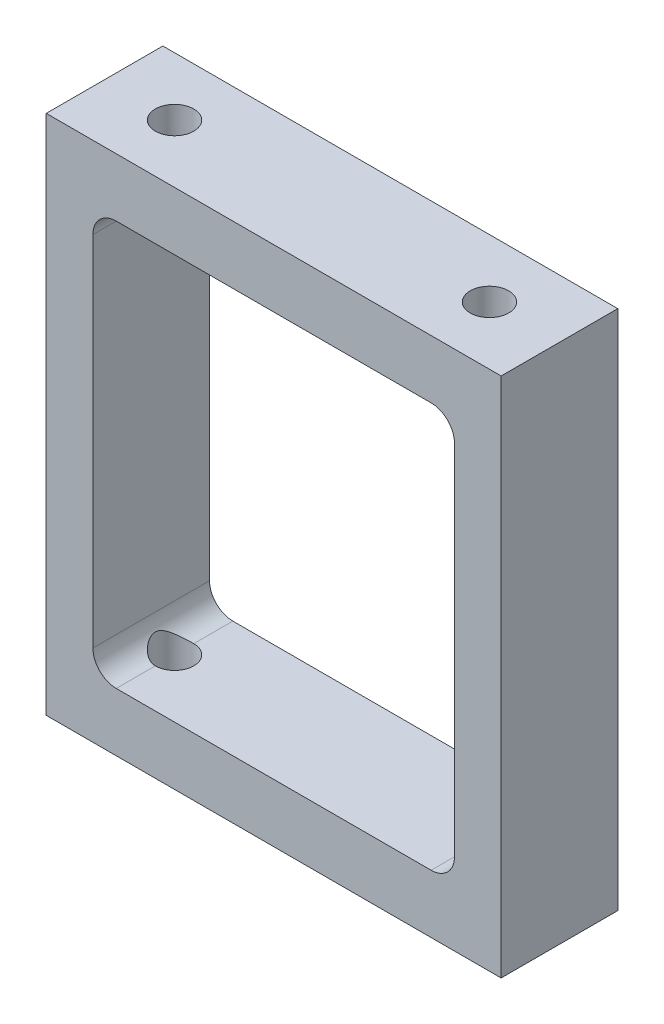
SolidWorks part; units mm, degrees
material "Alliage 1060"
ref_plane "Plan de face" through (0, 0, 0) normal (0, 0, 1) x (1, 0, 0)
ref_plane "Plan de dessus" through (0, 0, 0) normal (0, 1, 0) x (1, 0, 0)
ref_plane "Plan de droite" through (0, 0, 0) normal (1, 0, 0) x (0, 0, -1)
sketch "Esquisse1" plane through (0, 0, 0) normal (0, 1, 0) x (1, 0, 0)
  line L1 (0, 5) -> (39, 5)
  line L2 (0, 5) -> (0, -5)
  line L3 (0, -5) -> (39, -5)
  line L4 (39, 5) -> (39, -5)
  line L6 (-20.7377, 0) -> (13.7441, 0) construction
  dimension "D2" = 10
  dimension "D3" = 39
extrude "Extrusion1" add sketch "Esquisse1" along normal mid plane 44.7
hole_wizard "Trou taraudé M4x0.71" positions "Esquisse3" profile "Esquisse2" tap size "M4x0.7" standard "Ansi Métrique"
sketch "Esquisse3" plane through (0, -22.35, 0) normal (0, -1, 0) x (1, 0, 0)
  line L0 (0, -5) -> (0, 5) construction
  line L1 (39, 5) -> (39, -5) construction
  point P0 (33, 0)
  point P1 (6, 0)
  dimension "D1" = 6
  dimension "D2" = 6
sketch "Esquisse2" plane through (33, -22.35, 0) normal (1, 0, 0) x (0, 0, -1)
  line L0 (0, 0) -> (0, 11.0914)
  line L1 (0, 11.0914) -> (1.65, 10.1)
  line L2 (1.65, 10.1) -> (1.65, 0)
  line L5 (1.65, 0) -> (0, 0)
  line L10 (0, 11.0914) -> (-1.65, 10.1) construction
  line L11 (0, -6.35) -> (0, 107.95) construction
  dimension "Diamètre du trou pour taraudage" = 3.3
  dimension "Profondeur du trou pour taraudage" = 10.1
  dimension "Angle de pointe" = 118
cosmetic thread "Filetage de perçage1" parameters "D1"=8, "D2"=4
cosmetic thread "Filetage de perçage2" parameters "D1"=8, "D2"=4
hole_wizard "Trou taraudé M4x0.72" positions "Esquisse7" profile "Esquisse6" tap size "M4x0.7" standard "Ansi Métrique"
sketch "Esquisse7" plane through (0, 22.35, 0) normal (0, 1, 0) x (-1, 0, 0)
  circle A0 centre (-6, 0) radius 1.65 construction
  circle A1 centre (-33, 0) radius 1.65 construction
  point P0 (-6, 0)
  point P1 (-33, 0)
sketch "Esquisse6" plane through (6, 22.35, 0) normal (1, 0, 0) x (0, 0, 1)
  line L0 (0, 0) -> (0, 11.0914)
  line L1 (0, 11.0914) -> (1.65, 10.1)
  line L2 (1.65, 10.1) -> (1.65, 0)
  line L5 (1.65, 0) -> (0, 0)
  line L10 (0, 11.0914) -> (-1.65, 10.1) construction
  line L11 (0, -6.35) -> (0, 107.95) construction
  dimension "Diamètre du trou pour taraudage" = 3.3
  dimension "Profondeur du trou pour taraudage" = 10.1
  dimension "Angle de pointe" = 118
cosmetic thread "Filetage de perçage3" parameters "D1"=8, "D2"=4
cosmetic thread "Filetage de perçage4" parameters "D1"=8, "D2"=4
sketch "Esquisse8" plane through (0, 0, -5) normal (0, 0, -1) x (-1, 0, 0)
  line L0 (0, 22.35) -> (0, -22.35) construction
  line L1 (-33, 17.35) -> (-6, 17.35)
  line L2 (-35, 15.35) -> (-35, -15.35)
  line L3 (-33, -17.35) -> (-6, -17.35)
  line L4 (-4, 15.35) -> (-4, -15.35)
  line L5 (-39, 22.35) -> (-39, -22.35) construction
  line L6 (-39, 22.35) -> (0, 22.35) construction
  line L7 (-39, -22.35) -> (0, -22.35) construction
  arc A0 (-6, 17.35) -> (-4, 15.35) centre (-6, 15.35) cw
  arc A1 (-33, 17.35) -> (-35, 15.35) centre (-33, 15.35) ccw
  arc A2 (-35, -15.35) -> (-33, -17.35) centre (-33, -15.35) ccw
  arc A3 (-6, -17.35) -> (-4, -15.35) centre (-6, -15.35) ccw
  dimension "D5" = 2
  dimension "D1" = 4
  dimension "D2" = 4
  dimension "D3" = 5
  dimension "D4" = 5
extrude "Enlèv. mat.-Extru.1" cut sketch "Esquisse8" against normal through all
